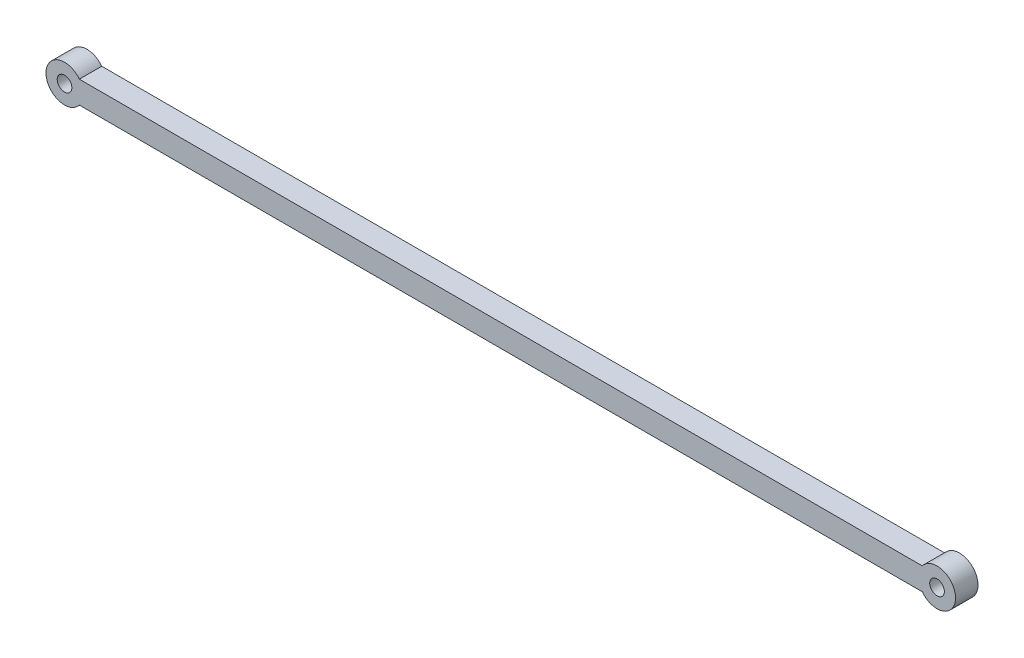
SolidWorks part; units mm, degrees
ref_plane "Front Plane" through (0, 0, 0) normal (0, 0, 1) x (1, 0, 0)
ref_plane "Top Plane" through (0, 0, 0) normal (0, 1, 0) x (1, 0, 0)
ref_plane "Right Plane" through (0, 0, 0) normal (1, 0, 0) x (0, 0, -1)
sketch "Sketch3" plane through (0, 0, 0) normal (0, 0, 1) x (1, 0, 0)
  line L0 (-625.3521, 0) -> (229.0483, 0) construction
  line L2 (-610.8885, 10.9763) -> (214.5847, 10.9763)
  line L3 (-610.8885, 10.9763) -> (-610.8885, -10.9763)
  line L4 (-610.8885, -10.9763) -> (214.5847, -10.9763)
  line L5 (214.5847, 10.9763) -> (214.5847, -10.9763)
  circle A0 centre (-625.3521, 0) radius 18.1569
  circle A1 centre (229.0483, 0) radius 18.1569
  point P9 (0, 0)
  point P10 (0, 0)
  dimension "D2" = 36.3139
  dimension "D1" = 854.4004
  dimension "D3" = 21.9525
extrude "Boss-Extrude1" add sketch "Sketch3" along normal mid plane 21.9525 contours L2 L5 L4 L3 | A0 | A1
sketch "Sketch4" plane through (0, 0, 10.9763) normal (0, 0, 1) x (1, 0, 0)
  circle A0 centre (-625.3521, 0) radius 7.1807
  circle A1 centre (229.0483, 0) radius 7.1807
  dimension "D1" = 14.3614
extrude "Cut-Extrude1" cut sketch "Sketch4" against normal through all
